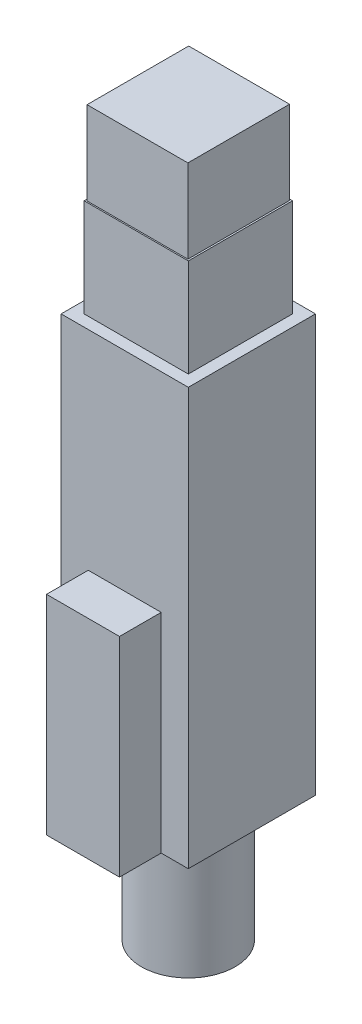
SolidWorks part; units mm, degrees
ref_plane "Front Plane" through (0, 0, 0) normal (0, 0, 1) x (1, 0, 0)
ref_plane "Top Plane" through (0, 0, 0) normal (0, 1, 0) x (1, 0, 0)
ref_plane "Right Plane" through (0, 0, 0) normal (1, 0, 0) x (0, 0, -1)
sketch "Sketch1" plane through (0, 0, 0) normal (0, 1, 0) x (1, 0, 0)
  circle A0 centre (0, 0) radius 2.25
extrude "Boss-Extrude1" add sketch "Sketch1" along normal blind 6
sketch "Sketch2" plane through (0, 6, 0) normal (0, 1, 0) x (1, 0, 0)
  line L1 (-3.05, -3.05) -> (3.05, -3.05)
  line L2 (-3.05, -3.05) -> (-3.05, 3.05)
  line L3 (-3.05, 3.05) -> (3.05, 3.05)
  line L4 (3.05, -3.05) -> (3.05, 3.05)
  line L5 (-3.05, -3.05) -> (3.05, 3.05) construction
  line L6 (-3.05, 3.05) -> (3.05, -3.05) construction
  point P0 (0, 0)
  dimension "D1" = 6.1
  dimension "D2" = 6.1
extrude "Boss-Extrude2" add sketch "Sketch2" along normal blind 20
sketch "Sketch3" plane through (0, 26, 0) normal (0, 1, 0) x (1, 0, 0)
  line L1 (-2.5, -2.5) -> (2.5, -2.5)
  line L2 (-2.5, -2.5) -> (-2.5, 2.5)
  line L3 (-2.5, 2.5) -> (2.5, 2.5)
  line L4 (2.5, -2.5) -> (2.5, 2.5)
  line L5 (-2.5, -2.5) -> (2.5, 2.5) construction
  line L6 (-2.5, 2.5) -> (2.5, -2.5) construction
  point P0 (0, 0)
  dimension "D1" = 5
  dimension "D2" = 5
extrude "Boss-Extrude3" add sketch "Sketch3" along normal blind 8.7
sketch "Sketch4" plane through (0, 34.7, 0) normal (0, 1, 0) x (1, 0, 0)
  line L1 (-2.4182, -2.4381) -> (2.4182, -2.4381)
  line L2 (-2.4182, -2.4381) -> (-2.4182, 2.4381)
  line L3 (-2.4182, 2.4381) -> (2.4182, 2.4381)
  line L4 (2.4182, -2.4381) -> (2.4182, 2.4381)
  line L5 (-2.4182, -2.4381) -> (2.4182, 2.4381) construction
  line L6 (-2.4182, 2.4381) -> (2.4182, -2.4381) construction
  point P0 (0, 0)
extrude "Cut-Extrude1" cut sketch "Sketch4" against normal blind 4 flip side to cut
sketch "Sketch5" plane through (0, 0, 3.05) normal (0, 0, 1) x (1, 0, 0)
  line L0 (-3.05, 6) -> (3.05, 6) construction
  line L1 (-1.75, 6) -> (1.75, 6)
  line L2 (-1.75, 6) -> (-1.75, 16)
  line L3 (-1.75, 16) -> (1.75, 16)
  line L4 (1.75, 6) -> (1.75, 16)
  line L5 (-3.05, 26) -> (-3.05, 6) construction
  line L6 (3.05, 26) -> (3.05, 6) construction
  dimension "D1" = 1.3
  dimension "D2" = 1.3
  dimension "D3" = 10
extrude "Boss-Extrude4" add sketch "Sketch5" along normal blind 2
